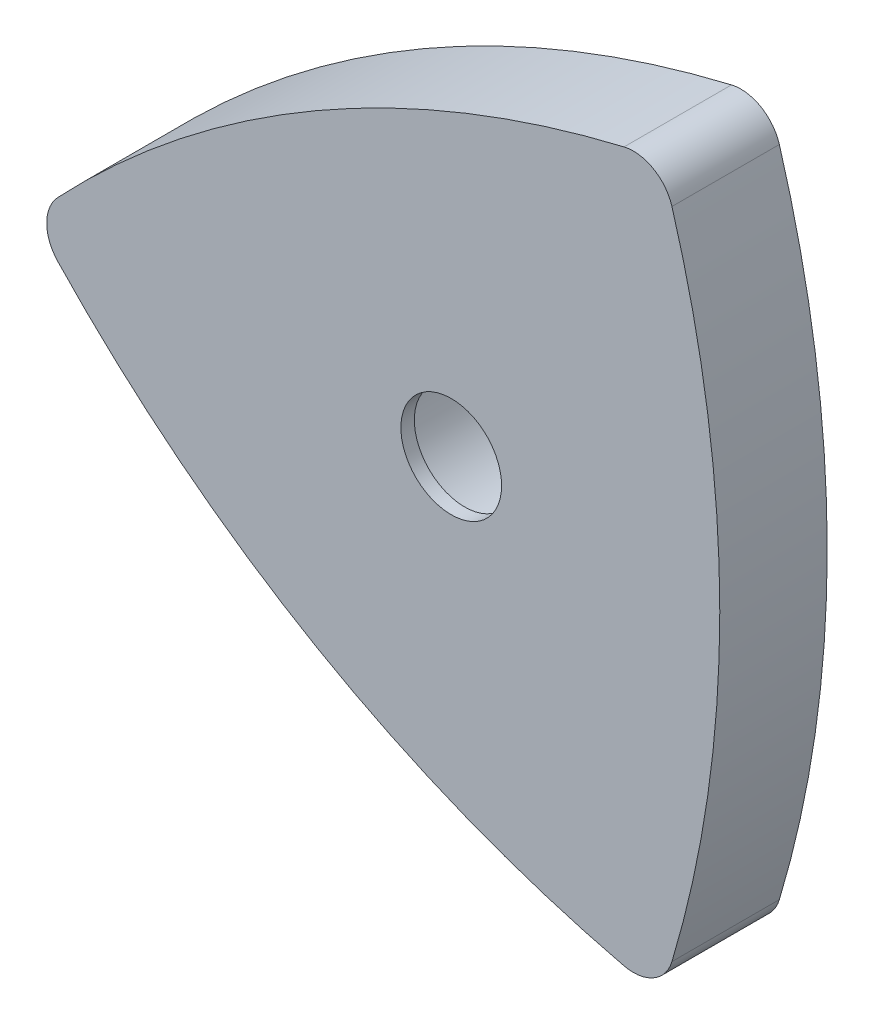
SolidWorks part; units mm, degrees
ref_plane "Face" through (0, 0, 0) normal (0, 0, 1) x (1, 0, 0)
ref_plane "Dessus" through (0, 0, 0) normal (0, 1, 0) x (1, 0, 0)
ref_plane "Droite" through (0, 0, 0) normal (1, 0, 0) x (0, 0, -1)
sketch "Esquisse1" plane through (0, 0, 0) normal (0, 0, 1) x (1, 0, 0)
  line L0 (-71, 0) -> (55, 0) construction
  line L2 (0, 0) -> (67.6625, -117.1949) construction
  arc A0 (25.7403, -52.8213) -> (-58.6147, -4.1189) centre (65, 112.5833) cw
  arc A1 (32.8744, -48.7024) -> (32.8744, 48.7024) centre (-130, 0) ccw
  arc A2 (-58.6147, 4.1189) -> (-58.6147, -4.1189) centre (-54.2518, 0) ccw
  arc A3 (25.7403, 52.8213) -> (-58.6147, 4.1189) centre (65, -112.5833) ccw
  arc A4 (32.8744, 48.7024) -> (25.7403, 52.8213) centre (27.1259, 46.9835) ccw
  arc A5 (32.8744, -48.7024) -> (25.7403, -52.8213) centre (27.1259, -46.9835) cw
  circle A6 centre (0, 0) radius 7.5
  point P13 (-62.3774, 0)
  point P17 (31.1887, 54.0204)
  point P21 (31.1887, -54.0204)
  dimension "D3" = 130
  dimension "D4" = 15
  dimension "D5" = 6
  dimension "D1" = 170
  dimension "D2" = 120
extrude "Base-Extrusion" add sketch "Esquisse1" along normal blind 16
sketch "Esquisse3" plane through (0, 0, 0) normal (0, 0, -1) x (-1, 0, 0)
  point P0 (0, 0)
sketch "Esquisse2" plane through (0, 0, 0) normal (0, 0, 1) x (1, 0, 0)
  circle A0 centre (0, 0) radius 13
  dimension "D1" = 26
extrude "Enlèv. mat.-Extru.2" cut sketch "Esquisse2" along normal blind 14
